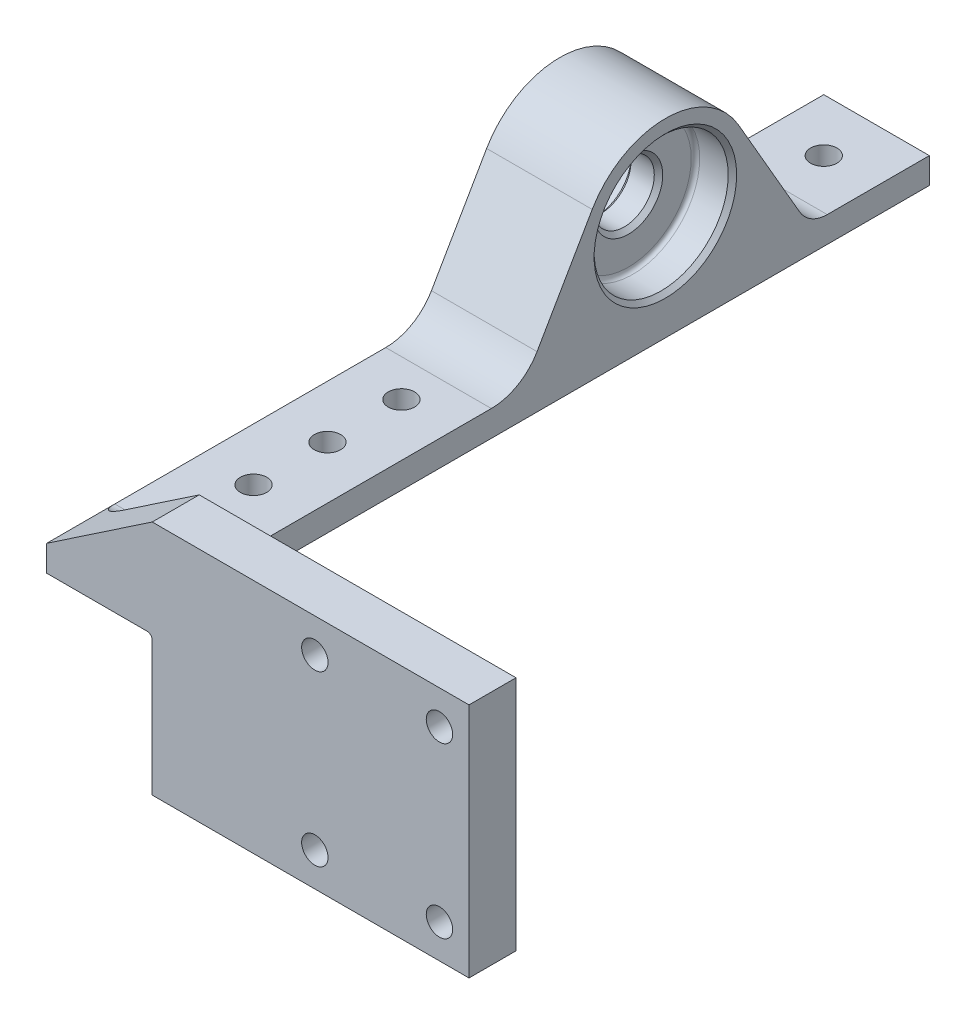
SolidWorks part; units mm, degrees
material "PLA"
ref_plane "Front Plane" through (0, 0, 0) normal (0, 0, 1) x (1, 0, 0)
ref_plane "Top Plane" through (0, 0, 0) normal (0, 1, 0) x (1, 0, 0)
ref_plane "Right Plane" through (0, 0, 0) normal (1, 0, 0) x (0, 0, -1)
sketch "Profile_Sketch_Gears" plane through (0, 0, 0) normal (1, 0, 0) x (0, 0, -1)
  line L0 (0, 0) -> (-152.4, 0) construction
  line L1 (-152.4, 0) -> (-152.4, -19.05) construction
  line L2 (-152.4, -19.05) -> (12.7, -19.05) construction
  line L3 (12.7, -19.05) -> (12.7, 101.6) construction
  line L4 (12.7, 101.6) -> (0, 101.6) construction
  line L5 (0, 101.6) -> (0, 0) construction
  line L6 (0, 38.1) -> (-16.51, 0) construction
  line L7 (-88.3232, -2.54) -> (-50.8, 12.7) construction
  circle A0 centre (-50.8, 12.7) radius 29.4524 construction
  circle A1 centre (-88.3232, -2.54) radius 15.4762 construction
  circle A2 centre (-50.8, 12.7) radius 26.9999 construction
  circle A3 centre (-88.3232, -2.54) radius 13.5 construction
  circle A4 centre (-50.8, 12.7) radius 58.42 construction
  dimension "D7" = 58.9049
  dimension "D8" = 30.9524
  dimension "D9" = 53.9999
  dimension "D10" = 26.9999
  dimension "D15" = 116.84
  dimension "D1" = 152.4
  dimension "D2" = 101.6
  dimension "D3" = 12.7
  dimension "D4" = 19.05
  dimension "D5" = 38.1
  dimension "D6" = 16.51
  dimension "D11" = 40.5
  dimension "D12" = 50.8
  dimension "D13" = 12.7
  dimension "D14" = 15.24
sketch "Profile_Sketch_Motor" plane through (0, 0, 0) normal (1, 0, 0) x (0, 0, -1)
  line L0 (-103.8172, 11.684) -> (-103.8172, -16.764) construction
  line L1 (-103.8172, -16.764) -> (-106.8652, -16.764) construction
  line L2 (-106.8652, -16.764) -> (-106.8652, 11.684) construction
  line L3 (-106.8652, 11.684) -> (-103.8172, 11.684) construction
  line L4 (-103.8172, 11.684) -> (-76.8932, 11.684) construction
  line L5 (-76.8932, 11.684) -> (-76.8932, -16.764) construction
  line L6 (-76.8932, -16.764) -> (-103.8172, -16.764) construction
  line L7 (-103.8172, -2.54) -> (-76.8932, -2.54) construction
  line L8 (-88.3232, 0.889) -> (-88.3232, -5.969) construction
  circle A0 centre (-88.3232, -2.54) radius 3.429 construction
  circle A1 centre (-80.7032, -2.54) radius 1 construction
  circle A2 centre (-95.9432, -2.54) radius 1 construction
  dimension "D4" = 6.858
  dimension "D7" = 2
  dimension "D1" = 3.048
  dimension "D2" = 28.448
  dimension "D3" = 26.924
  dimension "D5" = 11.43
  dimension "D6" = 15.24
sketch "Sketch2" plane through (0, 0, 0) normal (1, 0, 0) x (0, 0, -1)
  line L0 (-19.05, 0) -> (-112.5177, 0)
  line L1 (0, 0) -> (-152.4, 0) construction
  line L2 (-112.5177, 0) -> (-112.5177, 3.1115)
  line L3 (-112.5177, 3.1115) -> (-68.0677, 3.1115)
  line L4 (-19.05, 3.1115) -> (-19.05, 0)
  line L5 (0, 101.6) -> (0, 0) construction
  line L7 (-50.8, 22.86) -> (-50.8, 3.1115) construction
  line L9 (-19.05, 3.1115) -> (-33.5323, 3.1115)
  line L10 (-33.5323, 3.1115) -> (-42.0012, 17.78)
  line L11 (-68.0677, 3.1115) -> (-59.5988, 17.78)
  arc A0 (-42.0012, 17.78) -> (-59.5988, 17.78) centre (-50.8, 12.7) ccw
  circle A1 centre (-50.8, 12.7) radius 3.6195
  circle A2 centre (-50.8, 12.7) radius 6.35 construction
  point P9 (-25.333, 3.1115)
  dimension "D3" = 12.7
  dimension "0.65" = 20.32
  dimension "D4" = 7.239
  dimension "D1" = 19.05
  dimension "D2" = 3.1115
  dimension "D5" = 44.45
  dimension "D6" = 30
extrude "Bearing_Mount" add sketch "Sketch2" along normal mid plane 12.7
sketch "Sketch3" plane through (6.35, 0, 0) normal (1, 0, 0) x (0, 0, -1)
  circle A0 centre (-50.8, 12.7) radius 8.0645
  dimension "D1" = 16.129
extrude "Bearing_Hole" cut sketch "Sketch3" against normal blind 4.445
mirror "Mirror1" about plane through (0, 0, 0) normal (1, 0, 0) of "Bearing_Hole"
fillet "Fillet1" radius 6.35 1 edges at (0, 3.1115, 68.0677)
fillet "Fillet2" radius 0.508 2 edges at (-1.905, 12.7, 42.7355) (1.905, 12.7, 42.7355)
chamfer "Chamfer1" distance 0.508 angle 45 4 edges at (-6.35, 12.7, 42.7355) (-1.905, 12.7, 54.4195) (1.905, 12.7, 47.1805) (6.35, 12.7, 42.7355)
sketch "Sketch4" plane through (6.35, 0, 0) normal (1, 0, 0) x (0, 0, -1)
  line L0 (-112.5177, 11.684) -> (-112.5177, -16.764)
  line L1 (-112.5177, -16.764) -> (-106.8652, -16.764)
  line L2 (-106.8652, -16.764) -> (-106.8652, 11.684)
  line L3 (-106.8652, 11.684) -> (-112.5177, 11.684)
  dimension "D1" = 5.6525
extrude "Motor_Mount" add sketch "Sketch4" along normal blind 38.1
fillet "Fillet3" radius 3.81 1 edges at (0, 3.1115, 33.5323)
sketch "Sketch5" plane through (0, 0, 112.5177) normal (0, 0, 1) x (1, 0, 0)
  line L0 (6.35, 11.684) -> (-6.35, 3.1115)
  line L1 (-6.35, 3.1115) -> (-6.35, 0) construction
  line L2 (6.35, 3.1115) -> (-6.35, 3.1115) construction
  line L3 (-6.35, 3.1115) -> (6.35, 3.1115)
  line L4 (6.35, 3.1115) -> (6.35, 11.684)
extrude "Motor_Mount_Stiffener" add sketch "Sketch5" against normal up to surface (5.6525 mm away) up to face at (19.05, -1.1748, 106.8652)
sketch "Sketch6" plane through (0, 0, 106.8652) normal (0, 0, -1) x (-1, 0, 0)
  line L0 (-44.45, -2.54) -> (-6.35, -2.54) construction
  line L1 (-44.45, -16.764) -> (-44.45, 11.684) construction
  line L2 (-6.35, -16.764) -> (-6.35, 0) construction
  line L4 (-40.894, 7.62) -> (-25.908, 7.62) construction
  line L5 (-40.894, 7.62) -> (-40.894, -12.7) construction
  line L6 (-40.894, -12.7) -> (-25.908, -12.7) construction
  line L7 (-25.908, 7.62) -> (-25.908, -12.7) construction
  line L8 (-40.894, 7.62) -> (-25.908, -12.7) construction
  line L9 (-40.894, -12.7) -> (-25.908, 7.62) construction
  line L10 (-25.908, 7.62) -> (-22.86, 7.62) construction
  line L11 (-22.86, 7.62) -> (-22.86, -12.7) construction
  line L12 (-22.86, -12.7) -> (-25.908, -12.7) construction
  line L13 (-6.35, 5.0165) -> (-6.35, 17.78) construction
  circle A0 centre (-40.894, 7.62) radius 1.5875
  circle A1 centre (-25.908, 7.62) radius 1.5875
  circle A2 centre (-40.894, -12.7) radius 1.5875
  circle A3 centre (-25.908, -12.7) radius 1.5875
  point P6 (-33.401, -2.54)
  dimension "D5" = 3.175
  dimension "D6" = 3.175
  dimension "D7" = 3.175
  dimension "D8" = 3.175
  dimension "D1" = 14.986
  dimension "D2" = 20.32
  dimension "D4" = 3.048
  dimension "D3" = 16.51
extrude "Motor_Plate_Holes" cut sketch "Sketch6" against normal through all
fillet "Fillet4" radius 0.635 1 edges at (6.35, 0, 109.6915)
sketch "Sketch7" plane through (0, 3.1115, 0) normal (0, 1, 0) x (1, 0, 0)
  line L1 (0, -152.4) -> (0, 12.7) construction
  line L2 (6.35, -19.05) -> (-6.35, -19.05) construction
  line L3 (-6.35, -71.7339) -> (-6.35, -106.8652) construction
  line L4 (-6.35, -19.05) -> (-6.35, -31.3326) construction
  line L7 (-6.35, -42.0012) -> (-6.35, -59.5988)
  line L8 (-6.35, -59.5988) -> (6.35, -59.5988)
  line L9 (6.35, -59.5988) -> (6.35, -42.0012)
  line L10 (6.35, -42.0012) -> (-6.35, -42.0012)
  line L11 (-6.35, -42.0012) -> (-6.35, -59.5988) construction
  line L12 (-6.35, -59.5988) -> (6.35, -59.5988) construction
  line L13 (6.35, -59.5988) -> (6.35, -42.0012) construction
  line L14 (6.35, -42.0012) -> (-6.35, -42.0012) construction
  circle A0 centre (0, -25.4) radius 1.5875
  circle A1 centre (0, -76.2) radius 1.5875
  circle A2 centre (0, -85.09) radius 1.5875
  circle A3 centre (0, -93.98) radius 1.5875
  point P20 (6.35, -50.8)
  point P21 (-2.3253, -25.4)
  dimension "D5" = 3.175
  dimension "D1" = 3.175
  dimension "D4" = 3.175
  dimension "D12" = 3.175
  dimension "D3" = 6.35
  dimension "D7" = 6.35
  dimension "D8" = 6.35
  dimension "D9" = 25.4
  dimension "D10" = 8.89
  dimension "D11" = 8.89
  dimension "D2" = 6.35
  dimension "D13" = 25.4
  dimension "D14" = 76.2
  dimension "D15" = 85.09
  dimension "D16" = 93.98
extrude "Mount-Holes" cut sketch "Sketch7" against normal through all
fillet "Fillet5" radius 2.54 1 edges at (0, 3.1115, 106.8652)
equation "\"D6@Sketch6\"=\"D5@Sketch6\""
equation "\"D7@Sketch6\"=\"D5@Sketch6\""
equation "\"D8@Sketch6\"=\"D5@Sketch6\""
equation "\"D4@Sketch7\"=\"D1@Sketch7\""
equation "\"D5@Sketch7\"=\"D1@Sketch7\""
equation "\"D11@Sketch7\"=\"D10@Sketch7\""
equation "\"D12@Sketch7\"=\"D1@Sketch7\""
